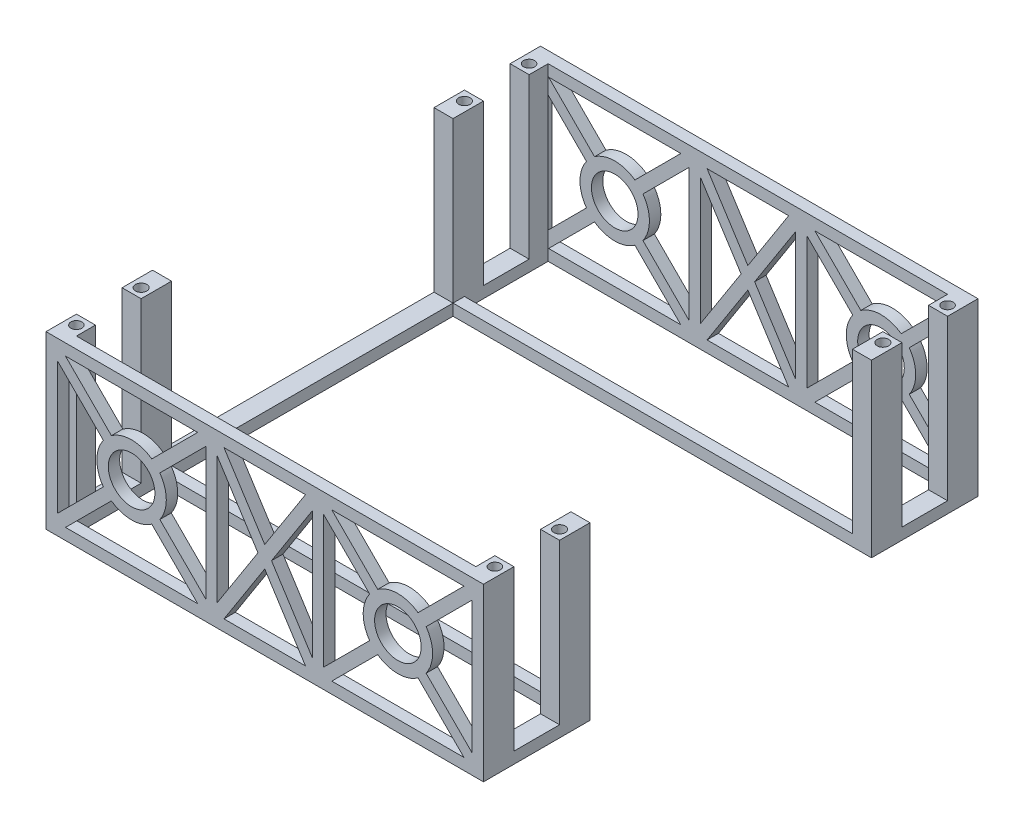
SolidWorks part; units mm, degrees
ref_plane "Front Plane" through (0, 0, 0) normal (0, 0, 1) x (1, 0, 0)
ref_plane "Top Plane" through (0, 0, 0) normal (0, 1, 0) x (1, 0, 0)
ref_plane "Right Plane" through (0, 0, 0) normal (1, 0, 0) x (0, 0, -1)
sketch "Sketch1" plane through (0, 0, 0) normal (0, 0, 1) x (1, 0, 0)
  line L0 (-39.9652, -52.0285) -> (-14.9652, -52.0285)
  line L1 (-100, 100) -> (100, 100) construction
  line L2 (-100, 100) -> (-100, -100) construction
  line L3 (-100, -100) -> (100, -100) construction
  line L4 (100, 100) -> (100, -100) construction
  line L5 (-84.9652, -52.0285) -> (-39.9652, -52.0285)
  line L6 (-84.9652, -52.0285) -> (-84.9652, -97.0285)
  line L7 (-84.9652, -97.0285) -> (-39.9652, -97.0285)
  line L9 (-84.9652, -52.0285) -> (-39.9652, -97.0285) construction
  line L10 (-84.9652, -97.0285) -> (-39.9652, -52.0285) construction
  line L11 (30.0348, -52.0285) -> (-14.9652, -52.0285)
  line L12 (30.0348, -52.0285) -> (30.0348, -97.0285)
  line L13 (30.0348, -97.0285) -> (-14.9652, -97.0285)
  line L15 (30.0348, -52.0285) -> (-14.9652, -97.0285) construction
  line L16 (30.0348, -97.0285) -> (-14.9652, -52.0285) construction
  line L17 (-14.9652, -97.0285) -> (-39.9652, -97.0285)
  line L18 (-39.9652, -94.0285) -> (-14.9652, -94.0285)
  line L19 (-39.9652, -55.0285) -> (-14.9652, -55.0285)
  line L20 (-39.9652, -55.0285) -> (-39.9652, -94.0285)
  line L21 (-14.9652, -55.0285) -> (-14.9652, -94.0285)
  line L22 (-39.9652, -52.0285) -> (-39.9652, -97.0285) construction
  line L23 (-14.9652, -97.0285) -> (-14.9652, -52.0285) construction
  line L24 (-27.4652, -52.0285) -> (-27.4652, -97.0285) construction
  line L25 (-39.9652, -55.0285) -> (-14.9652, -94.0285) construction
  line L26 (-14.9652, -55.0285) -> (-39.9652, -94.0285) construction
  line L27 (-79.8439, -94.0285) -> (-67.7691, -81.9537)
  line L32 (-79.3845, -57.6092) -> (-41.3424, -95.6513) construction
  line L33 (-81.9652, -55.0285) -> (-42.9652, -55.0285)
  line L38 (-79.9652, -52.0285) -> (-79.9652, -97.0285) construction
  line L39 (25.0348, -52.0285) -> (25.0348, -97.0285) construction
  line L40 (-81.9652, -55.0285) -> (-81.9652, -94.0285)
  line L41 (-81.9652, -94.0285) -> (-42.9652, -94.0285)
  line L42 (-42.9652, -55.0285) -> (-42.9652, -94.0285)
  line L43 (-81.9652, -55.0285) -> (-42.9652, -94.0285) construction
  line L44 (-81.9652, -94.0285) -> (-42.9652, -55.0285) construction
  line L45 (-11.9652, -94.0285) -> (27.0348, -94.0285)
  line L46 (-11.9652, -94.0285) -> (-11.9652, -55.0285)
  line L47 (-11.9652, -55.0285) -> (27.0348, -55.0285)
  line L48 (27.0348, -94.0285) -> (27.0348, -55.0285)
  line L49 (-11.9652, -94.0285) -> (27.0348, -55.0285) construction
  line L50 (-11.9652, -55.0285) -> (27.0348, -94.0285) construction
  line L51 (-57.1613, -81.9537) -> (-45.0865, -94.0285)
  line L52 (-42.9652, -91.9072) -> (-55.04, -79.8324)
  line L53 (-81.9652, -91.9072) -> (-69.8904, -79.8324)
  line L54 (-81.9652, -57.1498) -> (-69.8904, -69.2246)
  line L55 (-79.8439, -55.0285) -> (-67.7691, -67.1032)
  line L56 (-45.0865, -55.0285) -> (-57.1613, -67.1032)
  line L57 (-42.9652, -57.1498) -> (-55.04, -69.2246)
  line L58 (-27.4652, -77.308) -> (-38.1835, -94.0285)
  line L59 (-27.4652, -77.308) -> (-16.7469, -94.0285)
  line L60 (-14.9652, -91.249) -> (-25.6835, -74.5285)
  line L61 (-25.6835, -74.5285) -> (-14.9652, -57.808)
  line L62 (-16.7469, -55.0285) -> (-27.4652, -71.749)
  line L63 (-27.4652, -71.749) -> (-38.1835, -55.0285)
  line L64 (-39.9652, -57.808) -> (-29.2469, -74.5285)
  line L65 (-29.2469, -74.5285) -> (-39.9652, -91.249)
  line L66 (24.9135, -55.0285) -> (12.8387, -67.1032)
  line L67 (27.0348, -57.1498) -> (14.96, -69.2246)
  line L68 (27.0348, -91.9072) -> (14.96, -79.8324)
  line L69 (24.9135, -94.0285) -> (12.8387, -81.9537)
  line L70 (2.2309, -81.9537) -> (-9.8439, -94.0285)
  line L71 (-11.9652, -91.9072) -> (0.1096, -79.8324)
  line L72 (-11.9652, -57.1498) -> (0.1096, -69.2246)
  line L73 (-9.8439, -55.0285) -> (2.2309, -67.1032)
  circle A0 centre (-62.4652, -74.5285) radius 6.125
  circle A1 centre (7.5348, -74.5285) radius 6.125
  circle A2 centre (-62.4652, -74.5285) radius 9.125
  circle A3 centre (7.5348, -74.5285) radius 9.125
  point P23 (-27.4652, -74.5285)
  point P24 (-27.4652, -74.5285)
  dimension "D5" = 12.25
  dimension "D6" = 70
  dimension "D7" = 3
  dimension "D1" = 200
  dimension "D2" = 200
  dimension "D3" = 100
  dimension "D4" = 100
  dimension "D8" = 45
  dimension "D9" = 45
  dimension "D10" = 5
  dimension "D11" = 5
  dimension "D12" = 3
  dimension "D13" = 3
  dimension "D14" = 1.5
  dimension "D15" = 1.5
  dimension "D16" = 1.5
  dimension "D17" = 1.5
  dimension "D18" = 1.5
  dimension "D19" = 1.5
  dimension "D20" = 1.5
  dimension "D21" = 1.5
  dimension "D22" = 1.5
  dimension "D23" = 1.5
  dimension "D24" = 1.5
  dimension "D25" = 1.5
  dimension "D26" = 1.5
  dimension "D27" = 1.5
extrude "Boss-Extrude1" add sketch "Sketch1" along normal blind 3 contours L17 L13 L12 L11 L0 L5 L6 L7 L19 L21 L18 L20 A2 A3 | A2 L55 L33 L40 L54 | A2 L57 L42 L33 L56 | A2 A0 | A2 L51 L41 L42 L52 | A2 L53 L40 L41 L27 | L64 L65 L20 L18 L58 L59 L21 L60 L61 L19 L62 L63 | L70 A3 L71 L46 L45 | L72 A3 L73 L47 L46 | L66 A3 L67 L48 L47 | L68 A3 L69 L45 L48 | A3 A1
sketch "Sketch2" plane through (0, 0, 0) normal (0, 0, -1) x (-1, 0, 0)
  line L0 (-30.0348, -97.0285) -> (84.9652, -97.0285) construction
  line L1 (-30.0348, -52.0285) -> (-25.0348, -52.0285)
  line L2 (-30.0348, -52.0285) -> (-30.0348, -97.0285)
  line L3 (-30.0348, -97.0285) -> (-25.0348, -97.0285)
  line L4 (-25.0348, -52.0285) -> (-25.0348, -97.0285)
  line L5 (-30.0348, -52.0285) -> (84.9652, -52.0285) construction
  line L6 (84.9652, -97.0285) -> (79.9652, -97.0285)
  line L7 (84.9652, -97.0285) -> (84.9652, -52.0285)
  line L8 (84.9652, -52.0285) -> (79.9652, -52.0285)
  line L9 (79.9652, -97.0285) -> (79.9652, -52.0285)
  dimension "D1" = 5
  dimension "D2" = 5
extrude "Boss-Extrude2" add sketch "Sketch2" along normal blind 5
ref_plane "Plane1" through (0, -104.5285, 0) normal (0, -1, 0) x (-1, 0, 0)
sketch "Sketch3" plane through (0, -52.0285, 0) normal (0, 1, 0) x (1, 0, 0)
  line L0 (25.0348, 5) -> (30.0348, 0) construction
  line L1 (30.0348, -3) -> (30.0348, 5) construction
  line L2 (30.0348, 5) -> (25.0348, 0) construction
  line L3 (-79.9652, 5) -> (-84.9652, 0) construction
  line L4 (-84.9652, -3) -> (-84.9652, 5) construction
  line L5 (-84.9652, 5) -> (-79.9652, 0) construction
  circle A0 centre (-82.4652, 2.5) radius 1.45
  circle A1 centre (27.5348, 2.5) radius 1.45
  dimension "D1" = 2.9
  dimension "D2" = 2.9
extrude "Cut-Extrude1" cut sketch "Sketch3" against normal through all
ref_plane "Plane2" through (0, 0, -62) normal (0, 0, -1) x (-1, 0, 0)
sketch "Sketch4" plane through (0, 0, -5) normal (0, 0, -1) x (-1, 0, 0)
  line L0 (79.9652, -52.0285) -> (79.9652, -97.0285) construction
  line L1 (84.9652, -97.0285) -> (79.9652, -97.0285)
  line L2 (84.9652, -97.0285) -> (84.9652, -94.0285)
  line L3 (84.9652, -94.0285) -> (79.9652, -94.0285)
  line L4 (79.9652, -97.0285) -> (79.9652, -94.0285)
  line L5 (79.8439, -94.0285) -> (45.0865, -94.0285) construction
extrude "Boss-Extrude3" add sketch "Sketch4" along normal blind 122
mirror "Mirror3" about plane through (0, 0, -62) normal (0, 0, -1) of "Cut-Extrude1", "Boss-Extrude2", "Boss-Extrude1"
sketch "Sketch7" plane through (0, -97.0285, 0) normal (0, -1, 0) x (-1, 0, 0)
  line L1 (79.9652, 124) -> (79.9652, 0) construction
  line L2 (-30.0348, -3) -> (-30.0348, 127) construction
  line L3 (-30.0348, 22) -> (-30.0348, 25)
  line L4 (-30.0348, 25) -> (79.9652, 25)
  line L6 (79.9652, 25) -> (84.9652, 25)
  line L11 (84.9652, -3) -> (84.9652, 127) construction
  line L13 (-30.0348, 22) -> (-30.0348, 17)
  line L14 (-30.0348, 17) -> (-25.0348, 17)
  line L15 (-25.0348, 22) -> (-25.0348, 17)
  line L16 (84.9652, 25) -> (84.9652, 22)
  line L17 (84.9652, 22) -> (84.9652, 17)
  line L18 (84.9652, 17) -> (79.9652, 17)
  line L19 (79.9652, 17) -> (79.9652, 22)
  line L20 (79.9652, 22) -> (-25.0348, 22)
  line L21 (-25.0348, 5) -> (-25.0348, 0) construction
  line L22 (-30.0348, 17) -> (-25.0348, 22) construction
  line L23 (-30.0348, 22) -> (-25.0348, 17) construction
  line L24 (84.9652, 22) -> (79.9652, 17) construction
  line L25 (79.9652, 22) -> (84.9652, 17) construction
  line L26 (84.9652, 62) -> (-30.0348, 62) construction
  line L27 (79.9652, 102) -> (84.9652, 107) construction
  line L28 (84.9652, 102) -> (79.9652, 107) construction
  line L29 (-30.0348, 102) -> (-25.0348, 107) construction
  line L30 (-30.0348, 107) -> (-25.0348, 102) construction
  line L31 (79.9652, 102) -> (-25.0348, 102)
  line L32 (79.9652, 107) -> (79.9652, 102)
  line L33 (84.9652, 107) -> (79.9652, 107)
  line L34 (84.9652, 102) -> (84.9652, 107)
  line L35 (84.9652, 99) -> (84.9652, 102)
  line L36 (-25.0348, 102) -> (-25.0348, 107)
  line L37 (-30.0348, 107) -> (-25.0348, 107)
  line L38 (-30.0348, 102) -> (-30.0348, 107)
  line L39 (79.9652, 99) -> (84.9652, 99)
  line L40 (-30.0348, 99) -> (79.9652, 99)
  line L41 (-30.0348, 102) -> (-30.0348, 99)
  dimension "D1" = 5
  dimension "D2" = 3
  dimension "D5" = 11
extrude "Boss-Extrude5" add sketch "Sketch7" against normal blind 3
sketch "Sketch8" plane through (0, 0, -17) normal (0, 0, 1) x (1, 0, 0)
  line L1 (25.0348, -97.0285) -> (30.0348, -97.0285)
  line L2 (25.0348, -97.0285) -> (25.0348, -94.0285)
  line L3 (25.0348, -94.0285) -> (30.0348, -94.0285)
  line L4 (30.0348, -97.0285) -> (30.0348, -94.0285)
extrude "Boss-Extrude6" add sketch "Sketch8" along normal up to surface (12 mm away) up to face at (27.5348, -74.5285, -5)
sketch "Sketch9" plane through (0, 0, -107) normal (0, 0, -1) x (-1, 0, 0)
  line L1 (-25.0348, -97.0285) -> (-30.0348, -97.0285)
  line L2 (-25.0348, -97.0285) -> (-25.0348, -94.0285)
  line L3 (-25.0348, -94.0285) -> (-30.0348, -94.0285)
  line L4 (-30.0348, -97.0285) -> (-30.0348, -94.0285)
extrude "Boss-Extrude7" add sketch "Sketch9" along normal up to surface (12 mm away) up to face at (27.5348, -74.5285, -119)
sketch "Sketch10" plane through (0, -94.0285, 0) normal (0, 1, 0) x (1, 0, 0)
  line L0 (30.0348, 5) -> (30.0348, 25) construction
  line L5 (25.0348, 22) -> (30.0348, 22)
  line L10 (-84.9652, 119) -> (-84.9652, 5) construction
  line L11 (-79.9652, 102) -> (-84.9652, 102)
  line L12 (-79.9652, 102) -> (-79.9652, 107)
  line L13 (-79.9652, 107) -> (-84.9652, 107)
  line L14 (-84.9652, 102) -> (-84.9652, 107)
  line L15 (30.0348, 99) -> (30.0348, 119) construction
  line L16 (-79.9652, 22) -> (-84.9652, 22)
  line L17 (-79.9652, 22) -> (-79.9652, 17)
  line L18 (-79.9652, 17) -> (-84.9652, 17)
  line L19 (-84.9652, 22) -> (-84.9652, 17)
  line L20 (25.0348, 102) -> (30.0348, 102)
  line L21 (25.0348, 102) -> (25.0348, 107)
  line L22 (25.0348, 107) -> (30.0348, 107)
  line L23 (30.0348, 102) -> (30.0348, 107)
  line L24 (25.0348, 22) -> (25.0348, 17)
  line L25 (25.0348, 17) -> (30.0348, 17)
  line L26 (30.0348, 22) -> (30.0348, 17)
  line L28 (25.0348, 102) -> (30.0348, 102)
  line L29 (25.0348, 102) -> (25.0348, 99)
  line L30 (25.0348, 99) -> (30.0348, 99)
  line L31 (30.0348, 102) -> (30.0348, 99)
  line L32 (30.0348, 25) -> (25.0348, 25)
  line L33 (30.0348, 25) -> (30.0348, 22)
  line L34 (30.0348, 22) -> (25.0348, 22)
  line L35 (25.0348, 25) -> (25.0348, 22)
  line L36 (-79.9652, 102) -> (-84.9652, 102)
  line L37 (-79.9652, 102) -> (-79.9652, 99)
  line L38 (-79.9652, 99) -> (-84.9652, 99)
  line L39 (-84.9652, 102) -> (-84.9652, 99)
  line L40 (-79.9652, 25) -> (-84.9652, 25)
  line L41 (-79.9652, 25) -> (-79.9652, 22)
  line L42 (-79.9652, 22) -> (-84.9652, 22)
  line L43 (-84.9652, 25) -> (-84.9652, 22)
  line M12 (-79.9652, 99) -> (30.0348, 99)
  line M13 (30.0348, 99) -> (30.0348, 119)
  line M15 (25.0348, 119) -> (25.0348, 102)
  line M17 (-79.9652, 102) -> (-79.9652, 119)
  line M19 (-84.9652, 119) -> (-84.9652, 5)
  line M21 (-79.9652, 5) -> (-79.9652, 22)
  line M23 (25.0348, 22) -> (25.0348, 5)
  line M25 (30.0348, 5) -> (30.0348, 25)
  line M26 (30.0348, 25) -> (-79.9652, 25)
  dimension "D1" = 5
  dimension "D2" = 5
extrude "Boss-Extrude8" add sketch "Sketch10" along normal up to vertex (42 mm away) contours L38 L37 L11 M19 | L13 L11 M17 M19 | L41 L40 L16 M19 | L18 L16 M21 M19 | L35 L5 M26 M25 | L25 L5 M23 M25 | L22 L20 M15 M13 | L20 L29 M12 M13 up to point (-79.9652, -52.0285, -119)
sketch "Sketch13" plane through (0, -52.0285, 0) normal (0, 1, 0) x (1, 0, 0)
  line L0 (25.0348, 102) -> (30.0348, 102) construction
  line L1 (30.0348, 99) -> (30.0348, 107) construction
  line L2 (-79.9652, 102) -> (-84.9652, 102) construction
  line L3 (-84.9652, 107) -> (-84.9652, 99) construction
  line L4 (-79.9652, 22) -> (-84.9652, 22) construction
  line L5 (-84.9652, 25) -> (-84.9652, 17) construction
  line L6 (25.0348, 22) -> (30.0348, 22) construction
  line L7 (30.0348, 17) -> (30.0348, 25) construction
  line L8 (30.0348, 22) -> (25.0348, 17) construction
  line L9 (30.0348, 17) -> (25.0348, 22) construction
  line L10 (25.0348, 107) -> (30.0348, 102) construction
  line L11 (25.0348, 102) -> (30.0348, 107) construction
  line L12 (-84.9652, 102) -> (-79.9652, 107) construction
  line L13 (-79.9652, 102) -> (-84.9652, 107) construction
  line L14 (-84.9652, 17) -> (-79.9652, 22) construction
  line L15 (-79.9652, 17) -> (-84.9652, 22) construction
  circle A0 centre (27.5348, 19.5) radius 1.5
  circle A1 centre (27.5348, 104.5) radius 1.5
  circle A2 centre (-82.4652, 104.5) radius 1.5
  circle A3 centre (-82.4652, 19.5) radius 1.5
  dimension "D1" = 3
  dimension "D2" = 3
  dimension "D3" = 3
  dimension "D4" = 3
extrude "Cut-Extrude3" cut sketch "Sketch13" against normal through all
equation "\"AM3\"=3"
equation "\"D1@Sketch13\"=\"AM3\""
equation "\"D2@Sketch13\"=\"AM3\""
equation "\"D3@Sketch13\"=\"AM3\""
equation "\"D4@Sketch13\"=\"AM3\""
